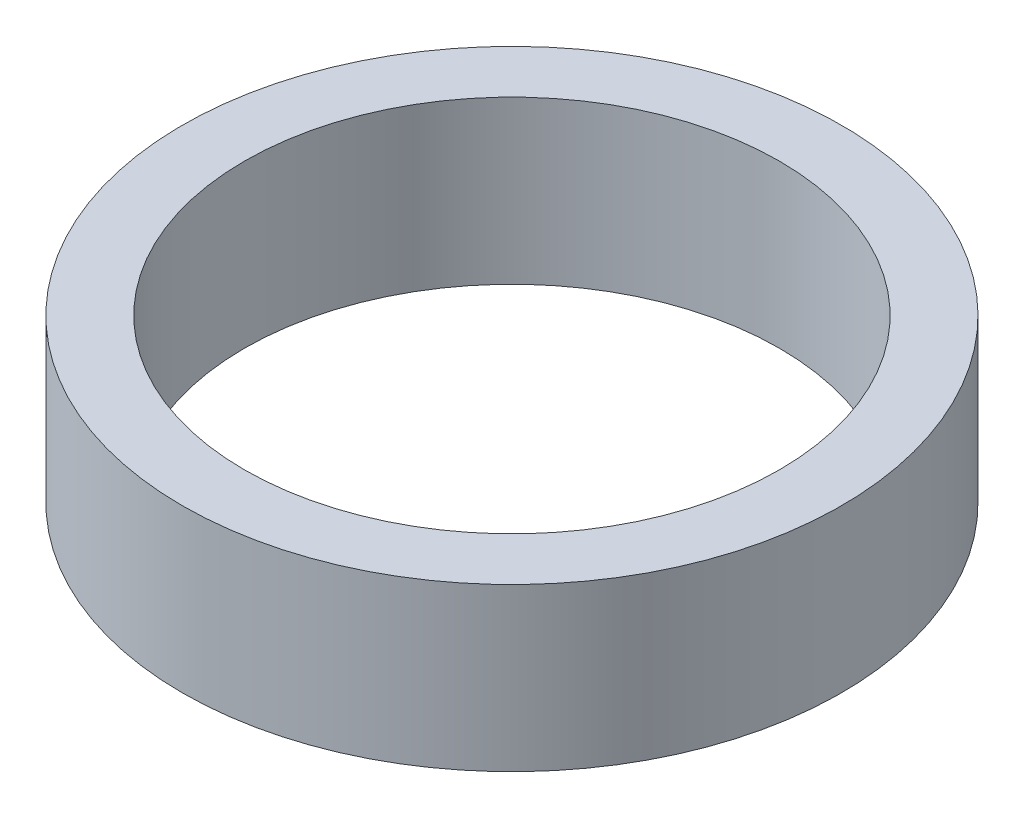
SolidWorks part; units mm, degrees
ref_plane "Plan de face" through (0, 0, 0) normal (0, 0, 1) x (1, 0, 0)
ref_plane "Plan de dessus" through (0, 0, 0) normal (0, 1, 0) x (1, 0, 0)
ref_plane "Plan de droite" through (0, 0, 0) normal (1, 0, 0) x (0, 0, -1)
sketch "Esquisse1" plane through (0, 0, 0) normal (0, 1, 0) x (1, 0, 0)
  circle A0 centre (0, 0) radius 4.95
  circle A1 centre (0, 0) radius 6.1
  dimension "D1" = 9.9
  dimension "D2" = 1.15
extrude "Spacer" add sketch "Esquisse1" along normal blind 3
